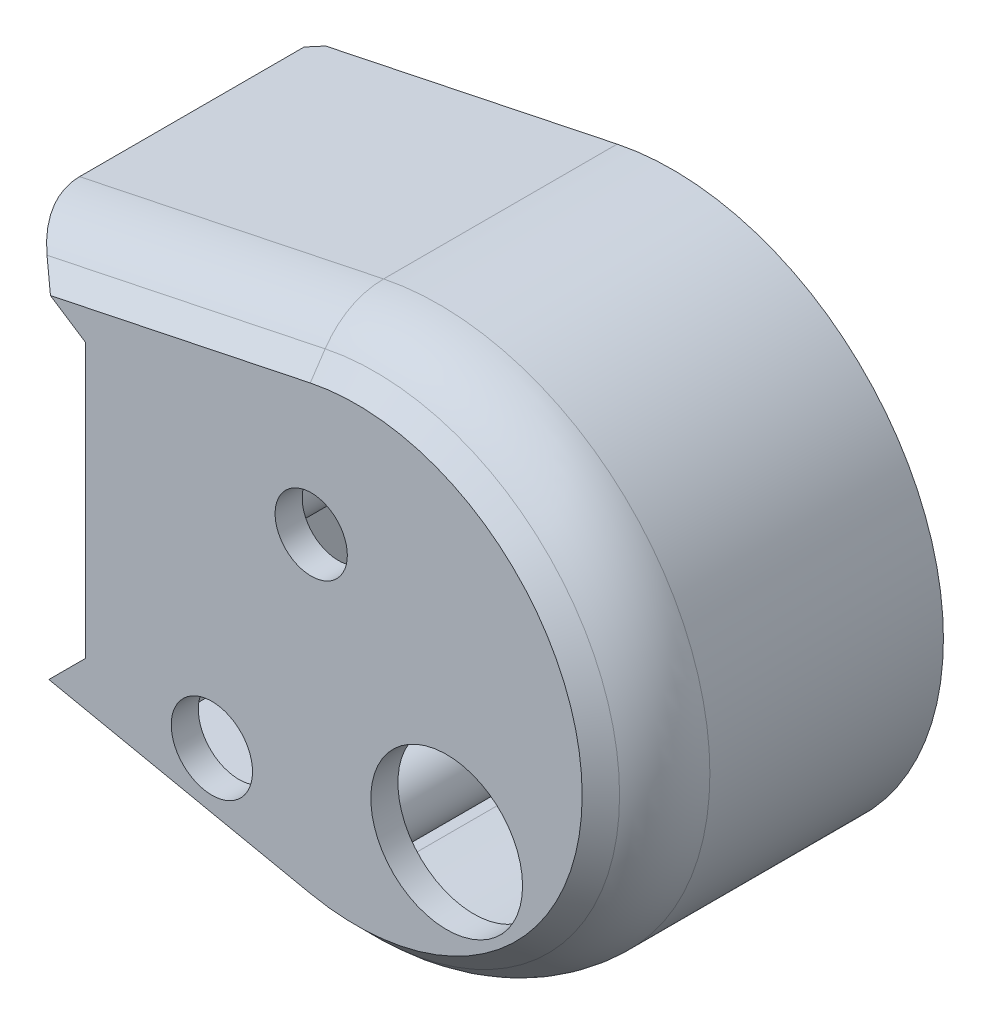
SolidWorks part; units mm, degrees
ref_plane "Alzado" through (0, 0, 0) normal (0, 0, 1) x (1, 0, 0)
ref_plane "Planta" through (0, 0, 0) normal (0, 1, 0) x (1, 0, 0)
ref_plane "Vista lateral" through (0, 0, 0) normal (1, 0, 0) x (0, 0, -1)
sketch "Croquis13" plane through (0, 0, 0) normal (0, 0, 1) x (1, 0, 0)
  line L0 (-6.1264, 29.3678) -> (-39.7893, 22.3453)
  line L1 (-39.7893, 22.3453) -> (-30, 15.9354)
  line L2 (-30, 15.9354) -> (-30, -14.3875)
  line L3 (-30, -14.3875) -> (-38.274, -22.6615)
  line L4 (-38.274, -22.6615) -> (-6.1264, -29.3678)
  arc A0 (-6.1264, -29.3678) -> (-6.1264, 29.3678) centre (0, 0) ccw
  circle A1 centre (-16, -16) radius 2.25 construction
  circle A2 centre (10, -12) radius 8.15 construction
  circle A3 centre (-5, 10) radius 7.9 construction
  circle A4 centre (-16, -16) radius 4.5
  circle A5 centre (10, -12) radius 8.4
  circle A6 centre (-5, 10) radius 4
  point P14 (0, 0)
  dimension "D1" = 30
  dimension "D2" = 8
  dimension "D3" = 16.8
  dimension "D4" = 9
extrude "Saliente-Extruir5" add sketch "Croquis13" against normal blind 35
sketch "Croquis14" plane through (0, 0, -35) normal (0, 0, -1) x (-1, 0, 0)
  line L6 (37.7634, -20.2141) -> (5.6159, -26.9205)
  line L7 (5.6159, 26.9205) -> (39.2787, 19.898)
  line L8 (27.5, -22.3552) -> (5.6159, -26.9205)
  line L9 (5.6159, 26.9205) -> (27.5, 22.3552)
  line L15 (27.5, -22.3552) -> (27.5, 22.3552)
  line L16 (30, 15.9354) -> (30, -14.3875) construction
  arc A3 (5.6159, 26.9205) -> (5.6159, -26.9205) centre (0, 0) ccw
  arc A4 (5.6159, 26.9205) -> (5.6159, -26.9205) centre (0, 0) ccw
  dimension "D2" = 2.5
  dimension "D1" = 2.5
extrude "Cortar-Extruir7" cut sketch "Croquis14" against normal offset from surface (32 mm away) 3 up to face at (-1, 10, 0)
chamfer "Chaflán6" distance 5 angle 45 3 edges at (-22.9579, 25.8566, 0) (30, 0, 0) (-22.2002, -26.0146, 0)
chamfer "Chaflán7" distance 2 angle 45 3 edges at (-16.558, 24.6378, -3) (-16.558, -24.6378, -3) (27.5, 0, -3)
sketch "Croquis15" plane through (0, 0, -3) normal (0, 0, -1) x (-1, 0, 0)
  circle A0 centre (0, 0) radius 22.5 construction
  circle A1 centre (22.5, 0) radius 4
  circle A2 centre (22.5, 0) radius 1.25
  circle A3 centre (6.9529, -21.3988) radius 1.25
  circle A4 centre (6.9529, -21.3988) radius 4
  circle A5 centre (-18.2029, -13.2252) radius 1.25 construction
  circle A6 centre (-18.2029, -13.2252) radius 4 construction
  circle A7 centre (-18.2029, 13.2252) radius 1.25
  circle A8 centre (-18.2029, 13.2252) radius 4
  circle A9 centre (6.9529, 21.3988) radius 1.25 construction
  circle A10 centre (6.9529, 21.3988) radius 4 construction
  dimension "D1" = 2.5
  dimension "D2" = 8
  dimension "D3" = 45
  dimension "D4" = 5
extrude "Saliente-Extruir9" add sketch "Croquis15" along normal up to surface (32 mm away) up to face at (-8.279, 0, -35)
chamfer "Chaflán8" distance 0.8 angle 45 3 edges at (19.4529, 13.2252, -35) (-21.25, 0, -35) (-5.7029, -21.3988, -35)
fillet "Redondeo1" radius 10 3 edges at (-22.2002, -26.0146, -5) (30, 0, -5) (-22.9579, 25.8566, -5)
chamfer "Chaflán9" distance 1 angle 45 3 edges at (-34.8946, 19.1404, -35) (-34.137, -18.5245, -35) (-30, 0.774, -35)
